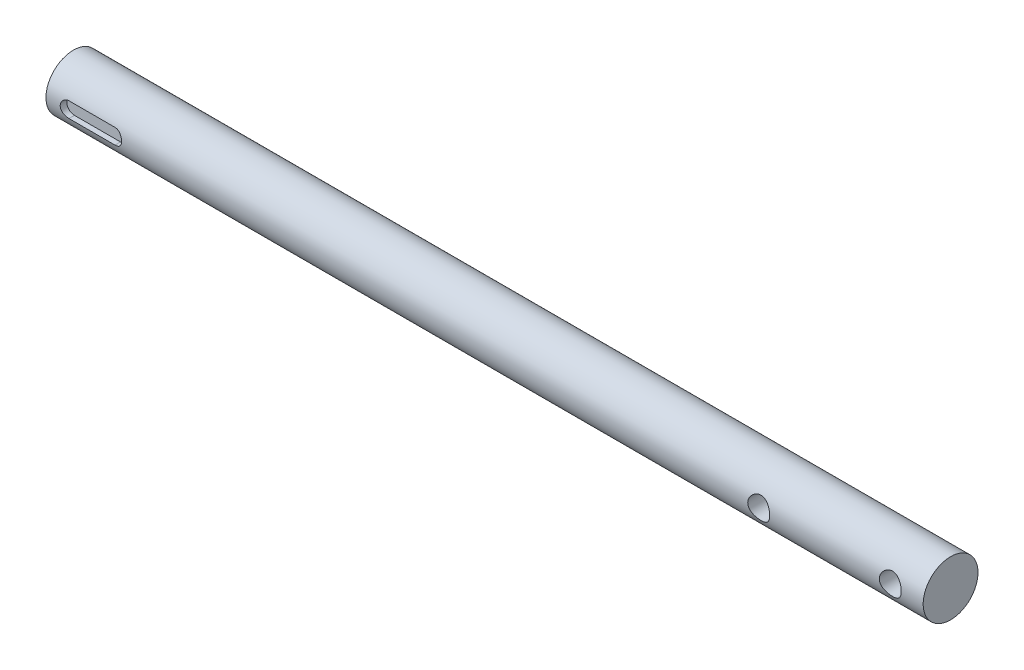
SolidWorks part; units mm, degrees
material "AISI 304"
ref_plane "Front Plane" through (0, 0, 0) normal (0, 0, 1) x (1, 0, 0)
ref_plane "Top Plane" through (0, 0, 0) normal (0, 1, 0) x (1, 0, 0)
ref_plane "Right Plane" through (0, 0, 0) normal (1, 0, 0) x (0, 0, -1)
sketch "Sketch1" plane through (0, 0, 0) normal (1, 0, 0) x (0, 0, -1)
  circle A0 centre (0, 0) radius 25
  dimension "D1" = 50
extrude "Boss-Extrude1" add sketch "Sketch1" along normal mid plane 800
sketch "Sketch2" plane through (0, 0, 0) normal (0, 0, 1) x (1, 0, 0)
  line L0 (400, -25) -> (400, 25) construction
  circle A0 centre (370, 0) radius 10
  circle A1 centre (250, 0) radius 10
  dimension "D1" = 20
  dimension "D2" = 20
  dimension "D3" = 30
  dimension "D4" = 150
extrude "Cut-Extrude1" cut sketch "Sketch2" against normal mid plane 320
ref_plane "Plane1" through (0, 0, 25) normal (0, 0, 1) x (1, 0, 0)
sketch "Sketch3" plane through (0, 0, 25) normal (0, 0, 1) x (1, 0, 0)
  line L0 (-380, 0) -> (-338, 0) construction
  line L1 (-380, 7) -> (-338, 7)
  line L2 (-380, -7) -> (-338, -7)
  line L3 (-400, 25) -> (-400, -25) construction
  arc A0 (-380, 7) -> (-380, -7) centre (-380, 0) ccw
  arc A1 (-338, -7) -> (-338, 7) centre (-338, 0) ccw
  point P3 (-359, 0)
  dimension "D1" = 14
  dimension "D2" = 42
  dimension "D3" = 20
extrude "Cut-Extrude2" cut sketch "Sketch3" against normal blind 6
